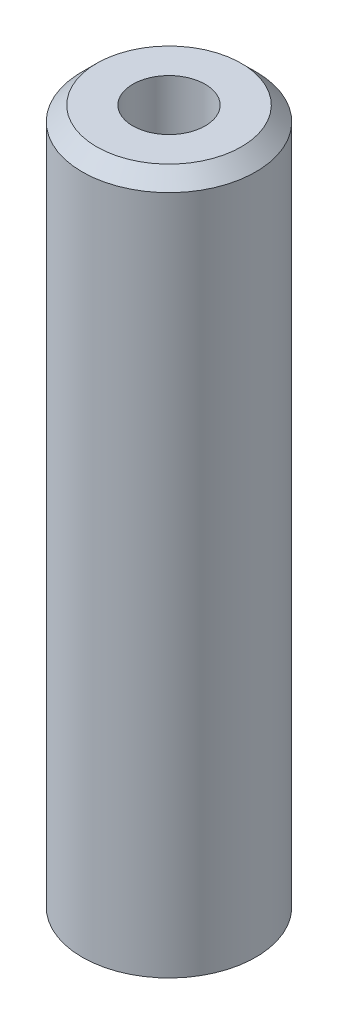
SolidWorks part; units mm, degrees
material "6061-O (SS)"
ref_plane "Alzado" through (0, 0, 0) normal (0, 0, 1) x (1, 0, 0)
ref_plane "Planta" through (0, 0, 0) normal (0, 1, 0) x (1, 0, 0)
ref_plane "Vista lateral" through (0, 0, 0) normal (1, 0, 0) x (0, 0, -1)
sketch "Croquis1" plane through (0, 0, 0) normal (0, 0, 1) x (1, 0, 0)
  line L0 (0, 48) -> (0, 0)
  line L1 (0, 0) -> (6, 0)
  line L2 (6, 0) -> (6, 47)
  line L3 (6, 47) -> (5, 48)
  line L5 (5, 48) -> (0, 48)
  dimension "D1" = 45
  dimension "D2" = 48
  dimension "D3" = 5
  dimension "D4" = 6
revolve "Revolución1" add sketch "Croquis1" angle 360 about L0
hole_wizard "Taladro roscado M61" positions "Croquis2" profile "Croquis3" tap size "M6" standard "DIN"
sketch "Croquis2" plane through (0, 48, 0) normal (0, 1, 0) x (1, 0, 0)
  point P0 (0, 0)
sketch "Croquis3" plane through (0, 48, 0) normal (1, 0, 0) x (0, 0, 1)
  line L0 (0, 0) -> (0, 11.5022)
  line L1 (0, 11.5022) -> (2.5, 10)
  line L2 (2.5, 10) -> (2.5, 0)
  line L5 (2.5, 0) -> (0, 0)
  line L10 (0, 11.5022) -> (-2.5, 10) construction
  line L11 (0, -6.35) -> (0, 107.95) construction
  dimension "Diámetro de perforador para roscar" = 5
  dimension "Profundidad de perforador para roscar" = 10
  dimension "Ángulo de perforador" = 118
cosmetic thread "Rosca de taladro1" parameters "D1"=9.95, "D2"=6
